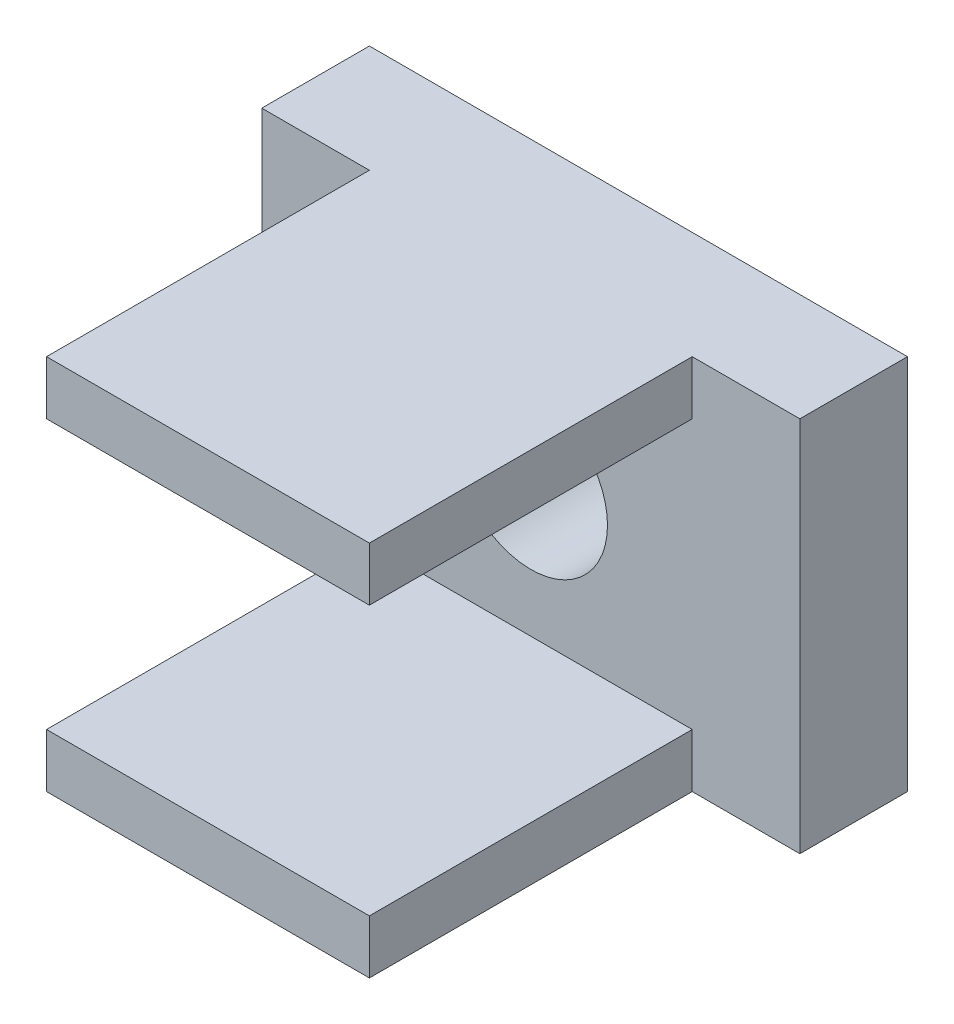
SolidWorks part; units mm, degrees
ref_plane "Front Plane" through (0, 0, 0) normal (0, 0, 1) x (1, 0, 0)
ref_plane "Top Plane" through (0, 0, 0) normal (0, 1, 0) x (1, 0, 0)
ref_plane "Right Plane" through (0, 0, 0) normal (1, 0, 0) x (0, 0, -1)
sketch "Sketch1" plane through (0, 0, 0) normal (0, 0, 1) x (1, 0, 0)
  line L1 (-5, -3.5) -> (5, -3.5)
  line L2 (-5, -3.5) -> (-5, 3.5)
  line L3 (-5, 3.5) -> (5, 3.5)
  line L4 (5, -3.5) -> (5, 3.5)
  line L5 (-5, -3.5) -> (5, 3.5) construction
  line L6 (-5, 3.5) -> (5, -3.5) construction
  point P0 (0, 0)
  dimension "D1" = 10
  dimension "D2" = 7
extrude "Boss-Extrude1" add sketch "Sketch1" along normal mid plane 2
sketch "Sketch2" plane through (0, 0, 1) normal (0, 0, 1) x (1, 0, 0)
  line L0 (5, 3.5) -> (-5, 3.5) construction
  line L1 (-3, 2.5) -> (3, 2.5)
  line L2 (-3, 2.5) -> (-3, 3.5)
  line L3 (-3, 3.5) -> (3, 3.5)
  line L4 (3, 2.5) -> (3, 3.5)
  line L5 (-3, 2.5) -> (3, 3.5) construction
  line L6 (-3, 3.5) -> (3, 2.5) construction
  line L7 (0, 0) -> (0, 5.625) construction
  point P0 (0, 3)
  point P10 (0, 0)
  dimension "D1" = 6
  dimension "D2" = 1
extrude "Boss-Extrude2" add sketch "Sketch2" along normal blind 6
mirror "Mirror1" about plane through (0, 0, 0) normal (0, 1, 0) of "Boss-Extrude2"
sketch "Sketch3" plane through (0, 0, 1) normal (0, 0, 1) x (1, 0, 0)
  circle A0 centre (0, 0) radius 1.425
  dimension "D1" = 2.85
extrude "Cut-Extrude1" cut sketch "Sketch3" against normal through all
